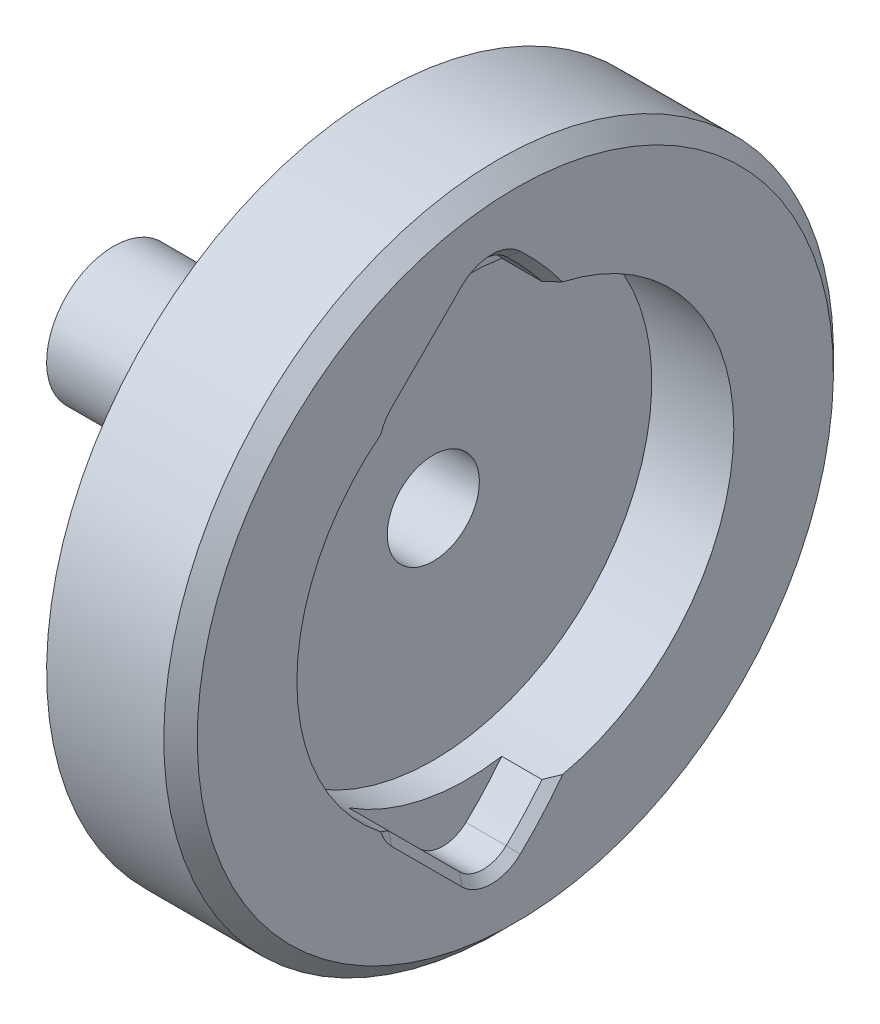
SolidWorks part; units mm, degrees
ref_plane "Alzado" through (0, 0, 0) normal (0, 0, 1) x (1, 0, 0)
ref_plane "Planta" through (0, 0, 0) normal (0, 1, 0) x (1, 0, 0)
ref_plane "Vista lateral" through (0, 0, 0) normal (1, 0, 0) x (0, 0, -1)
sketch "Croquis1" plane through (0, 0, 0) normal (0, 0, 1) x (1, 0, 0)
  line L0 (-16, 0) -> (-16, 4)
  line L1 (-16, 4) -> (0, 4)
  line L2 (0, 4) -> (0, 20)
  line L3 (0, 20) -> (8, 20)
  line L4 (8, 20) -> (8, 0)
  line L5 (8, 0) -> (-16, 0) construction
  line L6 (-16, 0) -> (8, 0)
  dimension "D1" = 40
  dimension "D2" = 8
  dimension "D3" = 16
  dimension "D4" = 8
revolve "Revolución1" add sketch "Croquis1" angle 360 about L5
sketch "Croquis2" plane through (8, 0, 0) normal (1, 0, 0) x (0, 0, -1)
  line L0 (0, 20) -> (0, -20) construction
  line L1 (-18.0333, 0) -> (-7.049, 10.9843) construction
  line L2 (-18.0333, 0) -> (-7.049, -10.9843) construction
  line L3 (-2.8392, 15.1941) -> (-7.049, 10.9843)
  line L4 (-7.049, -10.9843) -> (-2.8392, -15.1941)
  line L5 (-14.4333, 0) -> (-18.0333, 0) construction
  line L6 (-1.4538, 15.7797) -> (7.1943, 15.7797) construction
  line L7 (-1.4538, -15.7797) -> (8.9899, -15.7797) construction
  circle A0 centre (0, 0) radius 20 construction
  arc A1 (-0.0521, 15.2342) -> (-0.0521, -15.2342) centre (-14.4333, 0) cw
  arc A2 (-6.9884, 8.0978) -> (-6.9884, -8.0978) centre (-14.4333, 0) cw
  arc A3 (-0.0521, -15.2342) -> (-2.8392, -15.1941) centre (-1.425, -13.7799) cw
  arc A4 (-6.9884, -8.0978) -> (-7.049, -10.9843) centre (-5.6348, -9.5701) ccw
  arc A5 (-6.9884, 8.0978) -> (-7.049, 10.9843) centre (-5.6348, 9.5701) cw
  arc A6 (-0.0521, 15.2342) -> (-2.8392, 15.1941) centre (-1.425, 13.7799) ccw
  point P24 (-3.4333, 0)
  dimension "D1" = 20.95
  dimension "D2" = 11
  dimension "D4" = 2
  dimension "D3" = 90
  dimension "D5" = 3.6
extrude "Cortar-Extruir1" cut sketch "Croquis2" against normal blind 2.9
fillet "Redondeo1" radius 10 1 edges at (0, 4, 0)
sketch "Croquis3" plane through (-16, 0, 0) normal (-1, 0, 0) x (0, 0, 1)
  circle A0 centre (0, 0) radius 1.75
  dimension "D1" = 3.5
extrude "Cortar-Extruir2" cut sketch "Croquis3" against normal up to next
sketch "Croquis4" plane through (5.1, 0, 0) normal (1, 0, 0) x (0, 0, -1)
  circle A0 centre (0, 0) radius 2.75
  dimension "D1" = 5.5
extrude "Cortar-Extruir3" cut sketch "Croquis4" against normal offset from surface (18.1 mm away) 3 up to face at (-16, -1.75, 0)
chamfer "Chaflán1" distance 1 angle 45 1 edges at (8, 20, 0)
chamfer "Chaflán2" distance 0.5 angle 45 8 edges at (8, 0, 3.4333) (8, -9.5281, 7.6344) (8, 9.5281, 7.6344) (8, -13.0892, 4.9441) (8, 13.0892, 4.9441) (8, -15.7797, 1.4538) (8, 15.7797, 1.4538) (8, 0, -6.5167)
sketch "Croquis5" plane through (8, 0, 0) normal (1, 0, 0) x (0, 0, -1)
  circle A0 centre (0, 0) radius 13.05
  dimension "D1" = 26.1
extrude "Cortar-Extruir4" cut sketch "Croquis5" against normal offset from surface (4.9 mm away) 2 contours A0 up to face at (5.1, 2.75, 0) offset beyond the face yes
